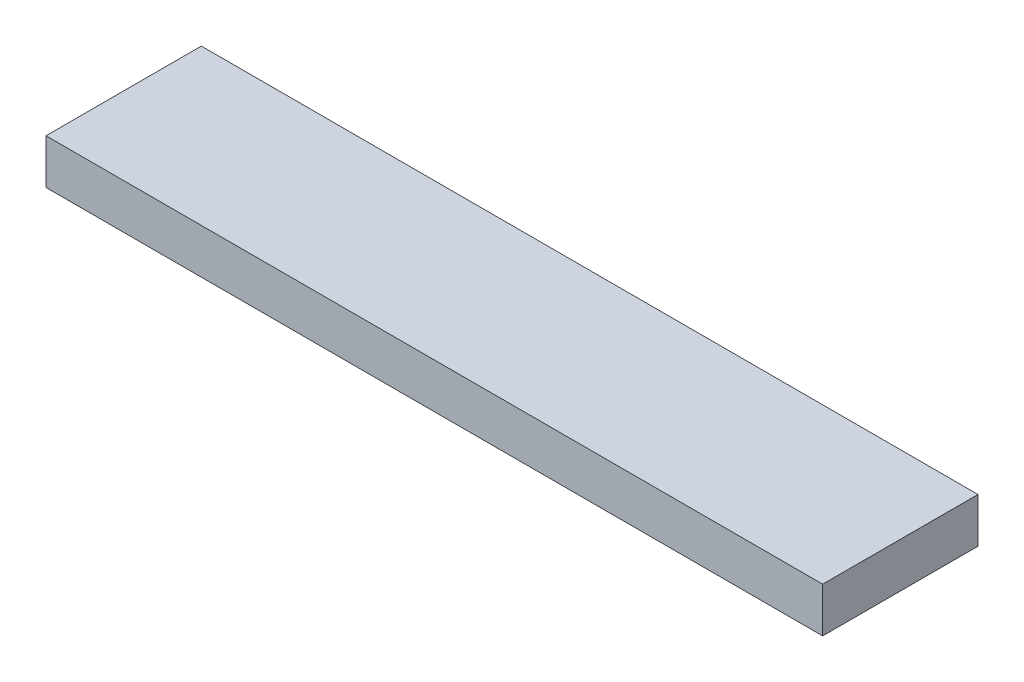
SolidWorks part; units mm, degrees
ref_plane "Front Plane" through (0, 0, 0) normal (0, 0, 1) x (1, 0, 0)
ref_plane "Top Plane" through (0, 0, 0) normal (0, 1, 0) x (1, 0, 0)
ref_plane "Right Plane" through (0, 0, 0) normal (1, 0, 0) x (0, 0, -1)
sketch "Sketch1" plane through (0, 0, 0) normal (0, 1, 0) x (1, 0, 0)
  line L1 (27.5, -5.5) -> (-27.5, -5.5)
  line L2 (27.5, -5.5) -> (27.5, 5.5)
  line L3 (27.5, 5.5) -> (-27.5, 5.5)
  line L4 (-27.5, -5.5) -> (-27.5, 5.5)
  line L5 (27.5, -5.5) -> (-27.5, 5.5) construction
  line L6 (27.5, 5.5) -> (-27.5, -5.5) construction
  point P0 (0, 0)
  dimension "D1" = 11
  dimension "D2" = 55
extrude "Boss-Extrude1" add sketch "Sketch1" along normal blind 3.175
